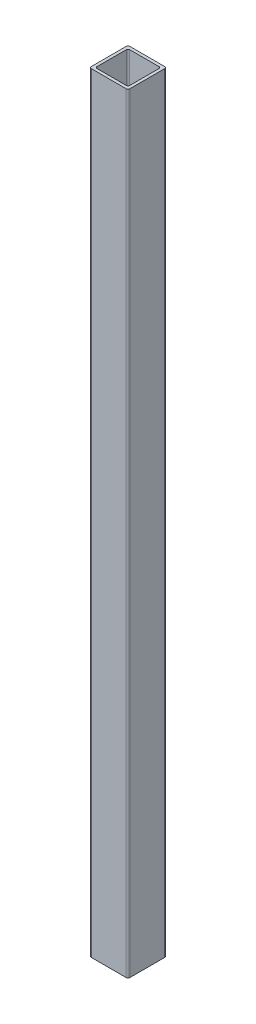
SolidWorks part; units mm, degrees
ref_plane "Front Plane" through (0, 0, 0) normal (0, 0, 1) x (1, 0, 0)
ref_plane "Top Plane" through (0, 0, 0) normal (0, 1, 0) x (1, 0, 0)
ref_plane "Right Plane" through (0, 0, 0) normal (1, 0, 0) x (0, 0, -1)
sketch "Sketch1" plane through (0, 0, 0) normal (0, 0, 1) x (1, 0, 0)
  line L0 (0, 0) -> (0, 1270)
  dimension "D1" = 1270
other "Square tube 2.5X2.5X.188 A500(1)"
ref_plane "Plane1" through (0, 0, 0) normal (0, 1, 0) x (-1, 0, 0)
sketch "Sketch11" plane through (0, 0, 0) normal (0, 1, 0) x (-1, 0, 0)
  line L0 (-26.9748, 0) -> (-31.75, 0) construction
  line L1 (28.575, -31.75) -> (-28.575, -31.75)
  line L2 (31.75, -28.575) -> (31.75, 28.575)
  line L3 (28.575, 31.75) -> (-28.575, 31.75)
  line L4 (-31.75, -28.575) -> (-31.75, 28.575)
  line L5 (31.75, -31.75) -> (-31.75, 31.75) construction
  line L6 (31.75, 31.75) -> (-31.75, -31.75) construction
  line L7 (24.2773, 26.9748) -> (-24.2773, 26.9748)
  line L8 (26.9748, 24.2773) -> (26.9748, -24.2773)
  line L9 (24.2773, -26.9748) -> (-24.2773, -26.9748)
  line L10 (-26.9748, 24.2773) -> (-26.9748, -24.2773)
  line L11 (26.9748, 26.9748) -> (-26.9748, -26.9748) construction
  line L12 (26.9748, -26.9748) -> (-26.9748, 26.9748) construction
  line L13 (0, -26.9748) -> (0, -31.75) construction
  line L14 (26.9748, -24.2773) -> (26.9748, -31.75) construction
  line L15 (26.9748, 0) -> (31.75, 0) construction
  line L16 (26.9748, -31.75) -> (31.75, -31.75) construction
  arc A0 (-24.2773, -26.9748) -> (-26.9748, -24.2773) centre (-24.2773, -24.2773) cw
  arc A1 (26.9748, -24.2773) -> (24.2773, -26.9748) centre (24.2773, -24.2773) cw
  arc A2 (24.2773, 26.9748) -> (26.9748, 24.2773) centre (24.2773, 24.2773) cw
  arc A3 (-24.2773, 26.9748) -> (-26.9748, 24.2773) centre (-24.2773, 24.2773) ccw
  arc A4 (28.575, -31.75) -> (31.75, -28.575) centre (28.575, -28.575) ccw
  arc A5 (31.75, 28.575) -> (28.575, 31.75) centre (28.575, 28.575) ccw
  arc A6 (-28.575, 31.75) -> (-31.75, 28.575) centre (-28.575, 28.575) ccw
  arc A7 (-28.575, -31.75) -> (-31.75, -28.575) centre (-28.575, -28.575) cw
  point P0 (0, 0)
  point P6 (0, 0)
  point P44 (0, 0)
  dimension "D2" = 2.6975
  dimension "D3" = 3.175
  dimension "D1" = 53.9496
  dimension "Outside Width" = 63.5
  dimension "Ouside Height" = 63.5
  dimension "Wall Thickness" = 4.7752
equation "\"D3@Sketch11\"=\"Outside Width@Sketch11\"*.05"
equation "\"D2@Sketch11\"=\"D1@Sketch11\"*.05"
